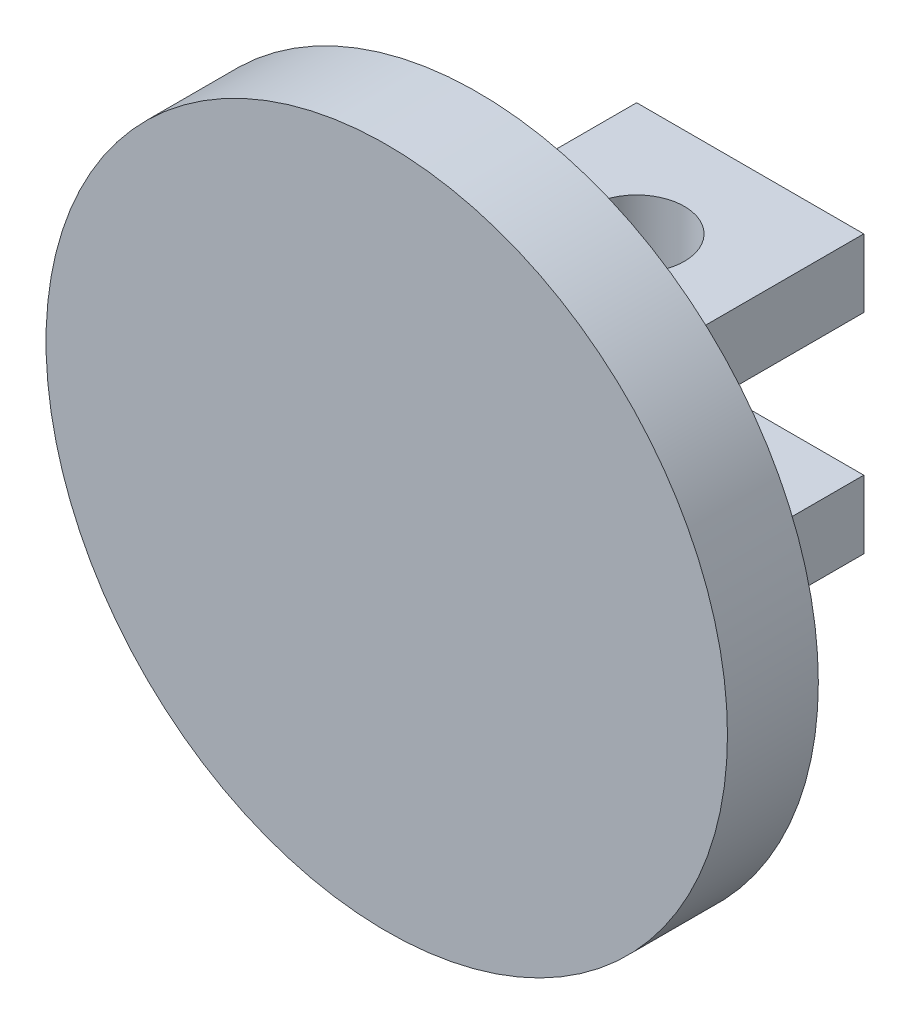
SolidWorks part; units mm, degrees
ref_plane "前视基准面" through (0, 0, 0) normal (0, 0, 1) x (1, 0, 0)
ref_plane "上视基准面" through (0, 0, 0) normal (0, 1, 0) x (1, 0, 0)
ref_plane "右视基准面" through (0, 0, 0) normal (1, 0, 0) x (0, 0, -1)
sketch "草图1" plane through (0, 0, 0) normal (0, 0, 1) x (1, 0, 0)
  circle A0 centre (0, 0) radius 15
  dimension "D1" = 30
extrude "凸台-拉伸1" add sketch "草图1" along normal blind 4
sketch "草图2" plane through (0, 0, 0) normal (0, 0, 1) x (1, 0, 0)
  line L0 (-12.8759, 0) -> (0, 0) construction
  line L1 (0, 0) -> (0, 8.756) construction
  line L2 (-5, -3.1) -> (5, -3.1)
  line L3 (-5, 6.1) -> (5, 6.1)
  line L4 (-5, 6.1) -> (-5, 3.1)
  line L5 (-5, 3.1) -> (5, 3.1)
  line L6 (5, 6.1) -> (5, 3.1)
  line L7 (-5, 6.1) -> (5, 3.1) construction
  line L8 (-5, 3.1) -> (5, 6.1) construction
  line L9 (5, -6.1) -> (5, -3.1)
  line L10 (-5, -6.1) -> (5, -6.1)
  line L11 (-5, -6.1) -> (-5, -3.1)
  line L12 (-5, -3.1) -> (5, -6.1) construction
  line L13 (-5, -6.1) -> (5, -3.1) construction
  point P3 (0, 4.6)
  point P13 (0, -4.6)
  dimension "D1" = 6.2
  dimension "D2" = 10
  dimension "D3" = 3
extrude "凸台-拉伸2" add sketch "草图2" against normal blind 12
sketch "草图3" plane through (0, 6.1, 0) normal (0, 1, 0) x (1, 0, 0)
  line L0 (0, 0) -> (0, 12) construction
  line L1 (5, 12) -> (-5, 12) construction
  circle A0 centre (0, 7) radius 2.1
  dimension "D2" = 4.2
  dimension "D1" = 5
extrude "切除-拉伸1" cut sketch "草图3" against normal blind 16
